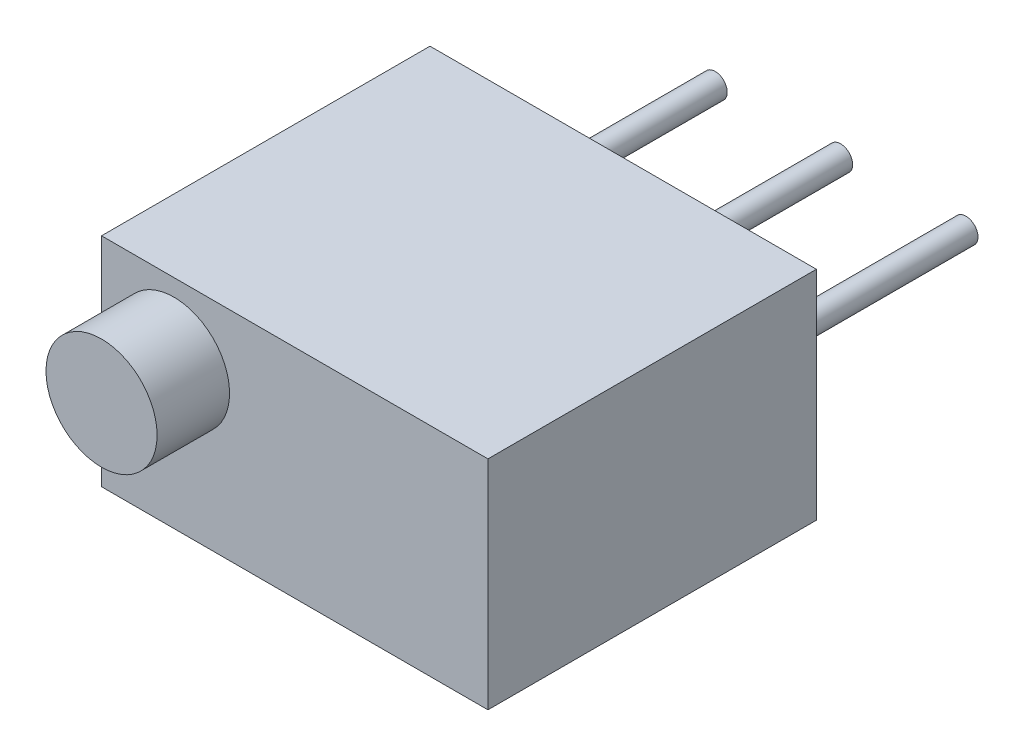
SolidWorks part; units mm, degrees
ref_plane "前视" through (0, 0, 0) normal (0, 0, 1) x (1, 0, 0)
ref_plane "上视" through (0, 0, 0) normal (0, 1, 0) x (1, 0, 0)
ref_plane "右视" through (0, 0, 0) normal (1, 0, 0) x (0, 0, -1)
sketch "草图1" plane through (0, 0, 0) normal (0, 1, 0) x (1, 0, 0)
  line L0 (0, 81.3418) -> (0, -101.3275) construction
  line L1 (-87.3375, 0) -> (113.7186, 0) construction
  line L3 (-4, 3.4) -> (4, 3.4)
  line L4 (-4, 3.4) -> (-4, -3.4)
  line L5 (-4, -3.4) -> (4, -3.4)
  line L6 (4, 3.4) -> (4, -3.4)
  dimension "D1" = 8
  dimension "D2" = 6.8
extrude "拉伸1" add sketch "草图1" along normal blind 4.5
sketch "草图3" plane through (0, 0, -3.4) normal (0, 0, -1) x (-1, 0, 0)
  line L0 (-5.1663, 2.25) -> (6.6013, 2.25) construction
  line L2 (0, 5.9307) -> (0, -2.165) construction
  circle A0 centre (0, 2.25) radius 0.25
  circle A1 centre (2.596, 2.25) radius 0.25
  circle A2 centre (-2.596, 2.25) radius 0.25
  dimension "D1" = 0.5
extrude "拉伸3" add sketch "草图3" along normal blind 4.5
sketch "草图4" plane through (0, 0, 3.4) normal (0, 0, 1) x (1, 0, 0)
  line L0 (-4, 4.5) -> (-4, 0) construction
  line L1 (-4, 4.5) -> (4, 4.5) construction
  circle A0 centre (-2.5, 3) radius 1.15
  dimension "D1" = 2.3
  dimension "D2" = 1.5
  dimension "D3" = 1.5
extrude "拉伸4" add sketch "草图4" along normal blind 1.5
